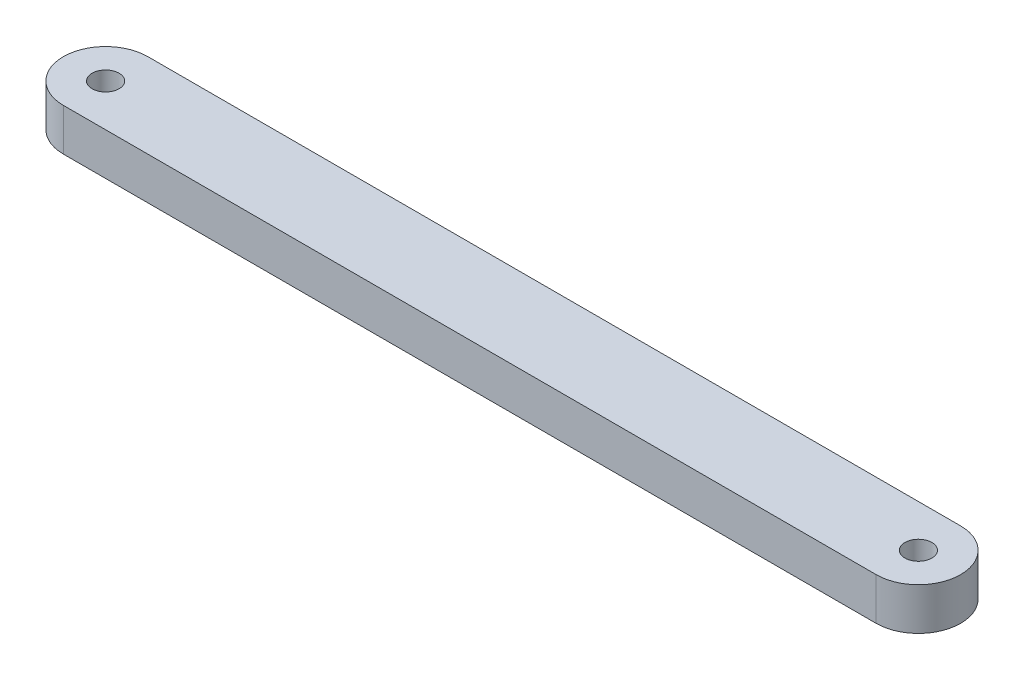
SolidWorks part; units mm, degrees
ref_plane "正面" through (0, 0, 0) normal (0, 0, 1) x (1, 0, 0)
ref_plane "平面" through (0, 0, 0) normal (0, 1, 0) x (1, 0, 0)
ref_plane "右側面" through (0, 0, 0) normal (1, 0, 0) x (0, 0, -1)
sketch "ｽｹｯﾁ1" plane through (0, 0, 0) normal (0, 1, 0) x (1, 0, 0)
  line L0 (-48.13, 0) -> (48.13, 0) construction
  line L1 (-48.13, 5) -> (48.13, 5)
  line L2 (-48.13, -5) -> (48.13, -5)
  arc A0 (-48.13, 5) -> (-48.13, -5) centre (-48.13, 0) ccw
  arc A1 (48.13, -5) -> (48.13, 5) centre (48.13, 0) ccw
  circle A2 centre (-48.13, 0) radius 1.6
  circle A3 centre (48.13, 0) radius 1.6
  point P3 (0, 0)
  dimension "D1" = 10
  dimension "D3" = 3.2
  dimension "D2" = 96.26
extrude "ﾎﾞｽ - 押し出し1" add sketch "ｽｹｯﾁ1" along normal blind 5
